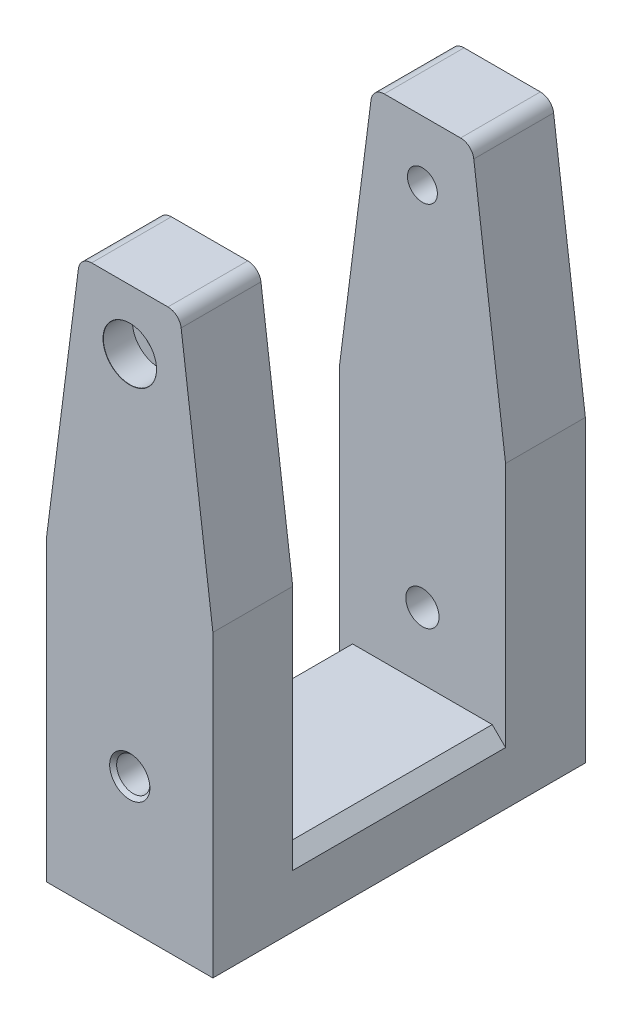
SolidWorks part; units mm, degrees
ref_plane "Front Plane" through (0, 0, 0) normal (0, 0, 1) x (1, 0, 0)
ref_plane "Top Plane" through (0, 0, 0) normal (0, 1, 0) x (1, 0, 0)
ref_plane "Right Plane" through (0, 0, 0) normal (1, 0, 0) x (0, 0, -1)
sketch "Sketch1" plane through (0, 0, 0) normal (0, 0, 1) x (1, 0, 0)
  line L0 (12.5, 0) -> (-12.5, 0)
  line L1 (-12.5, 0) -> (-12.5, 45)
  line L2 (-12.5, 45) -> (-7.5, 84)
  line L3 (-7.5, 84) -> (7.5, 84)
  line L4 (7.5, 84) -> (12.5, 45)
  line L5 (12.5, 45) -> (12.5, 0)
  line L6 (0, 0) -> (0, 84) construction
  dimension "D1" = 25
  dimension "D2" = 15
  dimension "D3" = 84
  dimension "D4" = 45
extrude "Boss-Extrude1" add sketch "Sketch1" along normal mid plane 56
sketch "Sketch2" plane through (12.5, 0, 0) normal (1, 0, 0) x (0, 0, -1)
  line L0 (-28, 84) -> (28, 84) construction
  line L1 (-16, 84) -> (16, 84)
  line L2 (-16, 84) -> (-16, 10)
  line L3 (-16, 10) -> (16, 10)
  line L4 (16, 84) -> (16, 10)
  line L5 (28, 45) -> (28, 84) construction
  line L6 (-28, 0) -> (28, 0) construction
  dimension "D1" = 12
  dimension "D2" = 32
  dimension "D3" = 10
extrude "Cut-Extrude1" cut sketch "Sketch2" against normal through all
sketch "Sketch5" plane through (0, 0, 28) normal (0, 0, 1) x (1, 0, 0)
  line L0 (0, 84) -> (0, 75) construction
  line L1 (7.5, 84) -> (-7.5, 84) construction
  dimension "D1" = 9
hole_wizard "CBORE for M4 Hex Socket Head Cap Screw1" positions "Sketch6" profile "Sketch7" counterbore size "M4" standard "ISO"
sketch "Sketch6" plane through (0, 0, 28) normal (0, 0, 1) x (1, 0, 0)
  point P0 (0, 75)
sketch "Sketch7" plane through (0, 75, 28) normal (1, 0, 0) x (0, -1, 0)
  line L0 (0, 0) -> (0, 21.3519)
  line L1 (0, 21.3519) -> (2.25, 20)
  line L2 (2.25, 20) -> (2.25, 4.4)
  line L3 (2.25, 4.4) -> (4, 4.4)
  line L5 (4, 4.4) -> (4, 0.025)
  line L6 (4, 0.025) -> (4.025, 0)
  line L7 (4.025, 0) -> (0, 0)
  line L8 (-4, 0.025) -> (-4.025, 0) construction
  line L10 (0, 21.3519) -> (-2.25, 20) construction
  line L11 (0, -6.35) -> (0, 107.95) construction
  dimension "Hole Dia." = 4.5
  dimension "Hole Depth" = 20
  dimension "C'Bore Dia." = 8
  dimension "C'Bore Depth" = 4.4
  dimension "Near C'Sink Dia." = 8.05
  dimension "Near C'Sink Angle" = 90
  dimension "Drill Angle" = 118
mirror "Mirror1" about plane through (0, 0, 0) normal (0, 0, 1) of "CBORE for M4 Hex Socket Head Cap Screw1"
hole_wizard "M6 Tapped Hole1" positions "Sketch8" profile "Sketch9" tap size "M6" standard "ISO"
sketch "Sketch8" plane through (0, 0, 28) normal (0, 0, 1) x (1, 0, 0)
  line L0 (0, 0) -> (0, 20) construction
  point P0 (0, 20)
  dimension "D1" = 20
sketch "Sketch9" plane through (0, 20, 28) normal (1, 0, 0) x (0, -1, 0)
  line L0 (0, 0) -> (0, 28.5022)
  line L1 (0, 28.5022) -> (2.5, 27)
  line L2 (2.5, 27) -> (2.5, 0.525)
  line L3 (2.5, 0.525) -> (3.025, 0)
  line L5 (3.025, 0) -> (0, 0)
  line L6 (-2.5, 0.525) -> (-3.025, 0) construction
  line L10 (0, 28.5022) -> (-2.5, 27) construction
  line L11 (0, -6.35) -> (0, 107.95) construction
  dimension "Tap Drill Dia." = 5
  dimension "Tap Drill Depth" = 27
  dimension "Near C'Sink Dia." = 6.05
  dimension "Near C'Sink Angle" = 90
  dimension "Drill Angle" = 118
cosmetic thread "Hole Thread1" parameters "D1"=12, "D2"=6
chamfer "Chamfer1" distance 2 angle 45 2 edges at (-12.5, 10, 0) (12.5, 10, 0)
fillet "Fillet1" radius 2 4 edges at (7.5, 84, -22) (-7.5, 84, -22) (-7.5, 84, 22) (7.5, 84, 22)
mirror "Mirror2" about plane through (0, 0, 0) normal (0, 0, 1) of "M6 Tapped Hole1"
